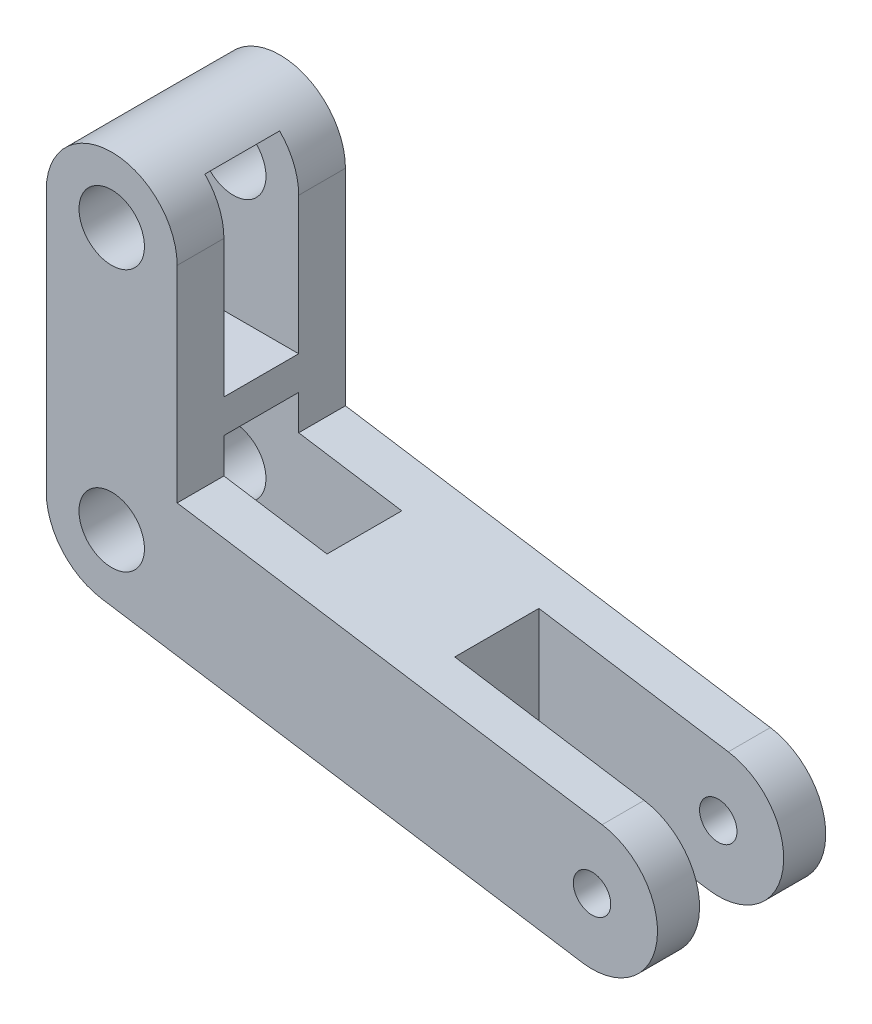
SolidWorks part; units mm, degrees
ref_plane "前视基准面" through (0, 0, 0) normal (0, 0, 1) x (1, 0, 0)
ref_plane "上视基准面" through (0, 0, 0) normal (0, 1, 0) x (1, 0, 0)
ref_plane "右视基准面" through (0, 0, 0) normal (1, 0, 0) x (0, 0, -1)
other "Configuration Table"
sketch "草图1" plane through (0, 0, 0) normal (0, 0, 1) x (1, 0, 0)
  line L0 (0, 14) -> (0, 1.75) construction
  line L1 (25.152, -7.4583) -> (-0.5385, -3.4583)
  line L2 (-3.5, 14) -> (-3.5, 0)
  line L3 (3.5, 14) -> (3.5, 2.9972)
  line L8 (26.2289, -0.5417) -> (3.5, 2.9972)
  line L9 (25.6905, -3) -> (25.6905, -4) construction
  circle A0 centre (0, 0) radius 1.75
  arc A1 (-3.5, 0) -> (-0.5385, -3.4583) centre (0, 0) ccw
  arc A2 (3.5, 14) -> (-3.5, 14) centre (0, 14) ccw
  circle A4 centre (0, 14) radius 1.75
  arc A5 (25.152, -7.4583) -> (26.2289, -0.5417) centre (25.6905, -4) ccw
  circle A6 centre (25.6905, -4) radius 1
  dimension "D1" = 14
  dimension "D2" = 3.5
  dimension "D3" = 7
  dimension "D8" = 2
  dimension "D4" = 26
  dimension "D5" = 4
extrude "凸台-拉伸1" add sketch "草图1" along normal mid plane 9
sketch "草图5" plane through (0, 0, 0) normal (0, 0, 1) x (1, 0, 0)
  line L1 (-5.6997, 16.4699) -> (3.5, 16.4699)
  line L2 (-5.6997, 16.4699) -> (-5.6997, 6.6567)
  line L3 (-5.6997, 6.6567) -> (3.5, 6.6567)
  line L4 (3.5, 16.4699) -> (3.5, 6.6567)
  line L5 (-5.6455, -5.6561) -> (9.0148, -5.6561)
  line L6 (-5.6455, -5.6561) -> (-5.6455, 4.8693)
  line L7 (-5.6455, 4.8693) -> (9.0148, 4.8693)
  line L8 (9.0148, -5.6561) -> (9.0148, 4.8693)
extrude "切除-拉伸3" cut sketch "草图5" against normal mid plane 4
sketch "草图6" plane through (0, 0, 0) normal (0, 0, 1) x (1, 0, 0)
  line L1 (35.2839, -10) -> (16.0971, -10)
  line L2 (35.2839, -10) -> (35.2839, 2)
  line L3 (35.2839, 2) -> (16.0971, 2)
  line L4 (16.0971, -10) -> (16.0971, 2)
  line L5 (35.2839, -10) -> (16.0971, 2) construction
  line L6 (35.2839, 2) -> (16.0971, -10) construction
  point P0 (25.6905, -4)
  dimension "D1" = 6
extrude "切除-拉伸4" cut sketch "草图6" against normal mid plane 4.5
